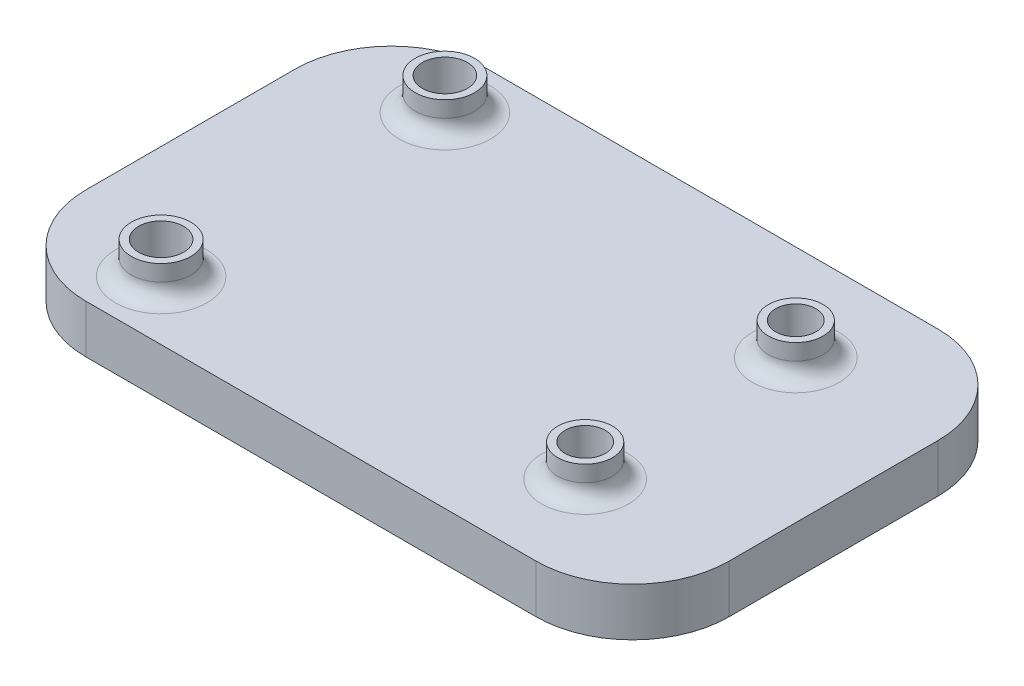
SolidWorks part; units mm, degrees
ref_plane "Front Plane" through (0, 0, 0) normal (0, 0, 1) x (1, 0, 0)
ref_plane "Top Plane" through (0, 0, 0) normal (0, 1, 0) x (1, 0, 0)
ref_plane "Right Plane" through (0, 0, 0) normal (1, 0, 0) x (0, 0, -1)
sketch "Sketch1" plane through (0, 0, 0) normal (0, 1, 0) x (1, 0, 0)
  line L0 (0, 12.5) -> (0, -12.5) construction
  line L1 (-20, 12.5) -> (20, 12.5)
  line L2 (-20, 12.5) -> (-20, -12.5)
  line L3 (-20, -12.5) -> (20, -12.5)
  line L4 (20, 12.5) -> (20, -12.5)
  line L5 (-20, 0) -> (20, 0) construction
  circle A0 centre (-13, 8.825) radius 1.4
  circle A1 centre (-13, -8.825) radius 1.4
  point P13 (-15, 8.825)
  dimension "D3" = 7
  dimension "D4" = 2.8
  dimension "D1" = 40
  dimension "D2" = 25
  dimension "D5" = 17.65
extrude "Boss-Extrude1" add sketch "Sketch1" along normal blind 3
sketch "Sketch2" plane through (0, 3, 0) normal (0, 1, 0) x (1, 0, 0)
  line L0 (0, 0) -> (20, 0) construction
  line L1 (20, -12.5) -> (20, 12.5) construction
  circle A0 centre (11.1, 6.55) radius 1.25
  circle A1 centre (-13, 8.825) radius 1.4 construction
  circle A2 centre (11.1, -6.55) radius 1.25
  dimension "D1" = 24.1
  dimension "D2" = 2.5
  dimension "D3" = 6.55
extrude "Cut-Extrude1" cut sketch "Sketch2" against normal through all
sketch "Sketch4" plane through (0, 3, 0) normal (0, 1, 0) x (1, 0, 0)
  circle A0 centre (-13, 8.825) radius 1.4
  circle A1 centre (-13, 8.825) radius 1.85
  circle A2 centre (11.1, 6.55) radius 1.25
  circle A3 centre (11.1, 6.55) radius 1.7
  circle A4 centre (11.1, -6.55) radius 1.25
  circle A5 centre (11.1, -6.55) radius 1.7
  circle A6 centre (-13, -8.825) radius 1.4
  circle A7 centre (-13, -8.825) radius 1.85
  circle A8 centre (-13, 8.825) radius 1.4 construction
  circle A9 centre (11.1, 6.55) radius 1.25 construction
  dimension "D1" = 3.7
  dimension "D2" = 3.4
extrude "Boss-Extrude2" add sketch "Sketch4" along normal blind 2
fillet "Fillet1" radius 1 4 edges at (11.1, 3, 8.25) (11.1, 3, -4.85) (-13, 3, -6.975) (-13, 3, 10.675)
sketch "Sketch5" plane through (0, 0, 0) normal (0, -1, 0) x (1, 0, 0)
  line L0 (-20, 12.5) -> (20, 12.5) construction
  line L1 (-11.47, 6.175) -> (-9.94, 8.825)
  line L2 (-9.94, 8.825) -> (-11.47, 11.475)
  line L3 (-11.47, 11.475) -> (-14.53, 11.475)
  line L4 (-14.53, 11.475) -> (-16.06, 8.825)
  line L5 (-16.06, 8.825) -> (-14.53, 6.175)
  line L6 (-14.53, 6.175) -> (-11.47, 6.175)
  line L7 (-11.47, -11.475) -> (-9.94, -8.825)
  line L8 (-9.94, -8.825) -> (-11.47, -6.175)
  line L9 (-11.47, -6.175) -> (-14.53, -6.175)
  line L10 (-14.53, -6.175) -> (-16.06, -8.825)
  line L11 (-16.06, -8.825) -> (-14.53, -11.475)
  line L12 (-14.53, -11.475) -> (-11.47, -11.475)
  circle A0 centre (-13, 8.825) radius 2.65 construction
  circle A1 centre (-13, -8.825) radius 2.65 construction
  dimension "D1" = 5.3
extrude "Cut-Extrude2" cut sketch "Sketch5" against normal blind 2
sketch "Sketch6" plane through (0, 0, 0) normal (0, -1, 0) x (1, 0, 0)
  line L0 (20, -12.5) -> (-20, -12.5) construction
  line L1 (12.2836, 4.5) -> (13.4671, 6.55)
  line L2 (13.4671, 6.55) -> (12.2836, 8.6)
  line L3 (12.2836, 8.6) -> (9.9164, 8.6)
  line L4 (9.9164, 8.6) -> (8.7329, 6.55)
  line L5 (8.7329, 6.55) -> (9.9164, 4.5)
  line L6 (9.9164, 4.5) -> (12.2836, 4.5)
  line L7 (12.2836, -8.6) -> (13.4671, -6.55)
  line L8 (13.4671, -6.55) -> (12.2836, -4.5)
  line L9 (12.2836, -4.5) -> (9.9164, -4.5)
  line L10 (9.9164, -4.5) -> (8.7329, -6.55)
  line L11 (8.7329, -6.55) -> (9.9164, -8.6)
  line L12 (9.9164, -8.6) -> (12.2836, -8.6)
  circle A0 centre (11.1, 6.55) radius 2.05 construction
  circle A1 centre (11.1, -6.55) radius 2.05 construction
  dimension "D1" = 4.1
extrude "Cut-Extrude3" cut sketch "Sketch6" against normal blind 1.4
fillet "Fillet2" radius 6 4 edges at (20, 1.5, 12.5) (20, 1.5, -12.5) (-20, 1.5, -12.5) (-20, 1.5, 12.5)
